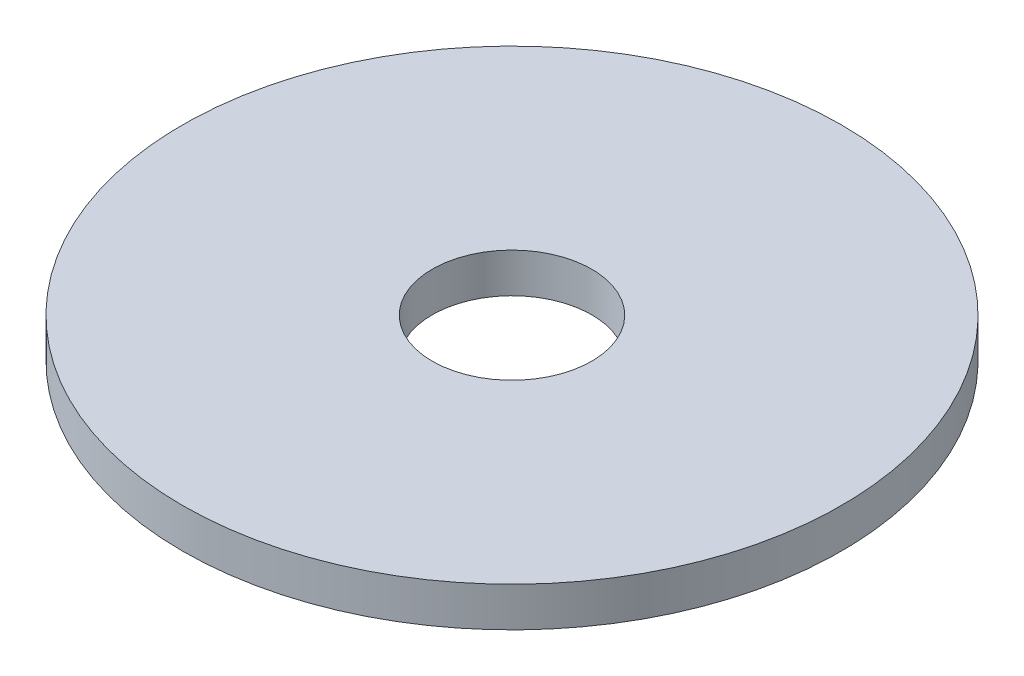
SolidWorks part; units mm, degrees
ref_plane "Front Plane" through (0, 0, 0) normal (0, 0, 1) x (1, 0, 0)
ref_plane "Top Plane" through (0, 0, 0) normal (0, 1, 0) x (1, 0, 0)
ref_plane "Right Plane" through (0, 0, 0) normal (1, 0, 0) x (0, 0, -1)
sketch "Sketch1" plane through (0, 0, 0) normal (0, 1, 0) x (1, 0, 0)
  circle A0 centre (0, 0) radius 6.05
  circle A1 centre (0, 0) radius 25
  dimension "D1" = 12.1
  dimension "D2" = 50
extrude "Boss-Extrude1" add sketch "Sketch1" along normal blind 3
